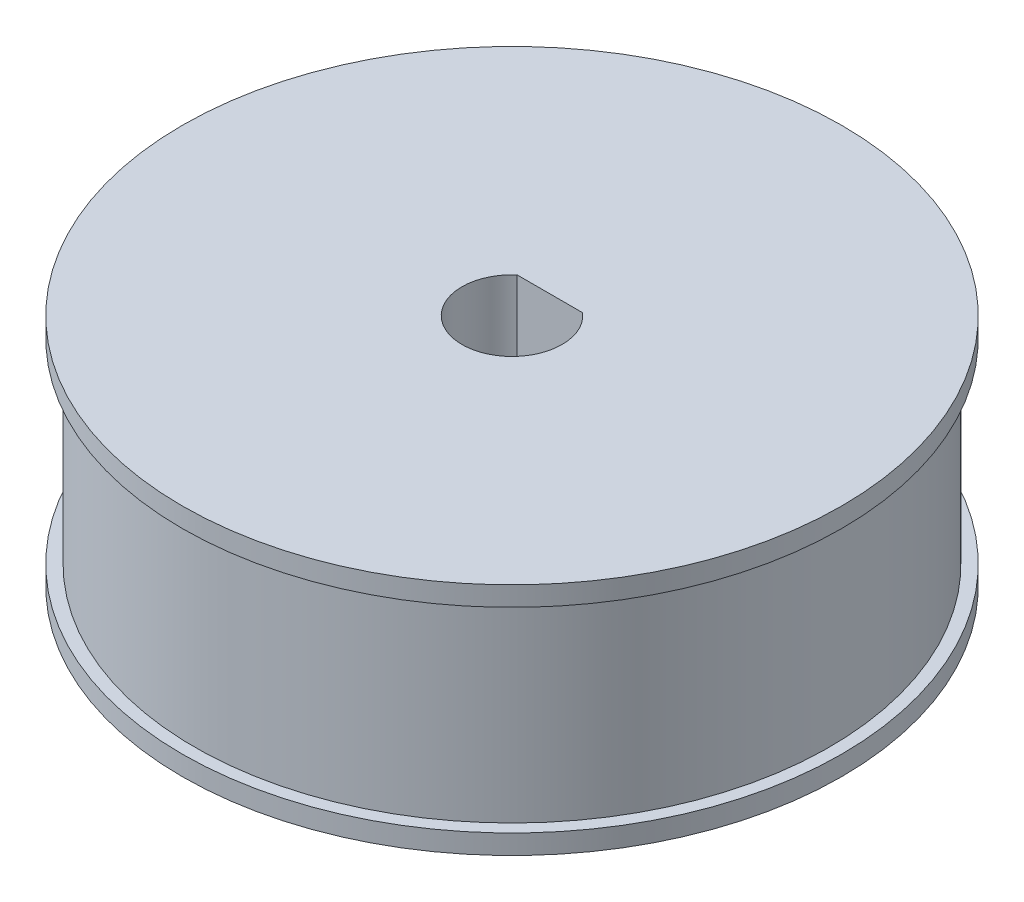
SolidWorks part; units mm, degrees
ref_plane "Front Plane" through (0, 0, 0) normal (0, 0, 1) x (1, 0, 0)
ref_plane "Top Plane" through (0, 0, 0) normal (0, 1, 0) x (1, 0, 0)
ref_plane "Right Plane" through (0, 0, 0) normal (1, 0, 0) x (0, 0, -1)
sketch "Sketch1" plane through (0, 0, 0) normal (0, 0, 1) x (1, 0, 0)
  line L0 (0, 0) -> (0, 8323.9074) construction
  line L1 (2, 0) -> (13.5, 0)
  line L2 (13.5, 0) -> (13.5, 0.8)
  line L3 (13.5, 0.8) -> (13, 0.8)
  line L4 (13, 0.8) -> (13, 8.8)
  line L5 (13, 8.8) -> (13.5, 8.8)
  line L6 (13.5, 8.8) -> (13.5, 9.6)
  line L7 (13.5, 9.6) -> (2, 9.6)
  line L8 (2, 9.6) -> (2, 0)
  point P11 (13.9046, 0)
  dimension "D1" = 4
  dimension "D2" = 26
  dimension "D3" = 8
  dimension "D4" = 0.8
  dimension "D5" = 0.5
revolve "Revolve1" add sketch "Sketch1" angle 360 about L0
sketch "Sketch2" plane through (0, 9.6, 0) normal (0, 1, 0) x (1, 0, 0)
  line L0 (-1.3229, 1.5) -> (1.3229, 1.5)
  circle A0 centre (0, 0) radius 2 construction
  arc A1 (-1.3229, 1.5) -> (1.3229, 1.5) centre (0, 0) cw
  point P4 (0, -2)
  point P6 (0, 1.5)
  dimension "D1" = 3.5
extrude "Boss-Extrude1" add sketch "Sketch2" against normal up to surface (9.6 mm away) up to face at (0, 0, -13.5)
sketch "Sketch4" plane through (0, 0, 0) normal (0, -1, 0) x (1, 0, 0)
  line L3 (-1.3416, -1.55) -> (1.3416, -1.55)
  line L4 (-1.3416, -1.55) -> (1.3416, -1.55)
  arc A2 (1.3416, -1.55) -> (-1.3416, -1.55) centre (0, 0) ccw
  arc A3 (1.3416, -1.55) -> (-1.3416, -1.55) centre (0, 0) ccw
  dimension "D1" = 0.05
extrude "Cut-Extrude1" cut sketch "Sketch4" against normal through all both and the other way through all
